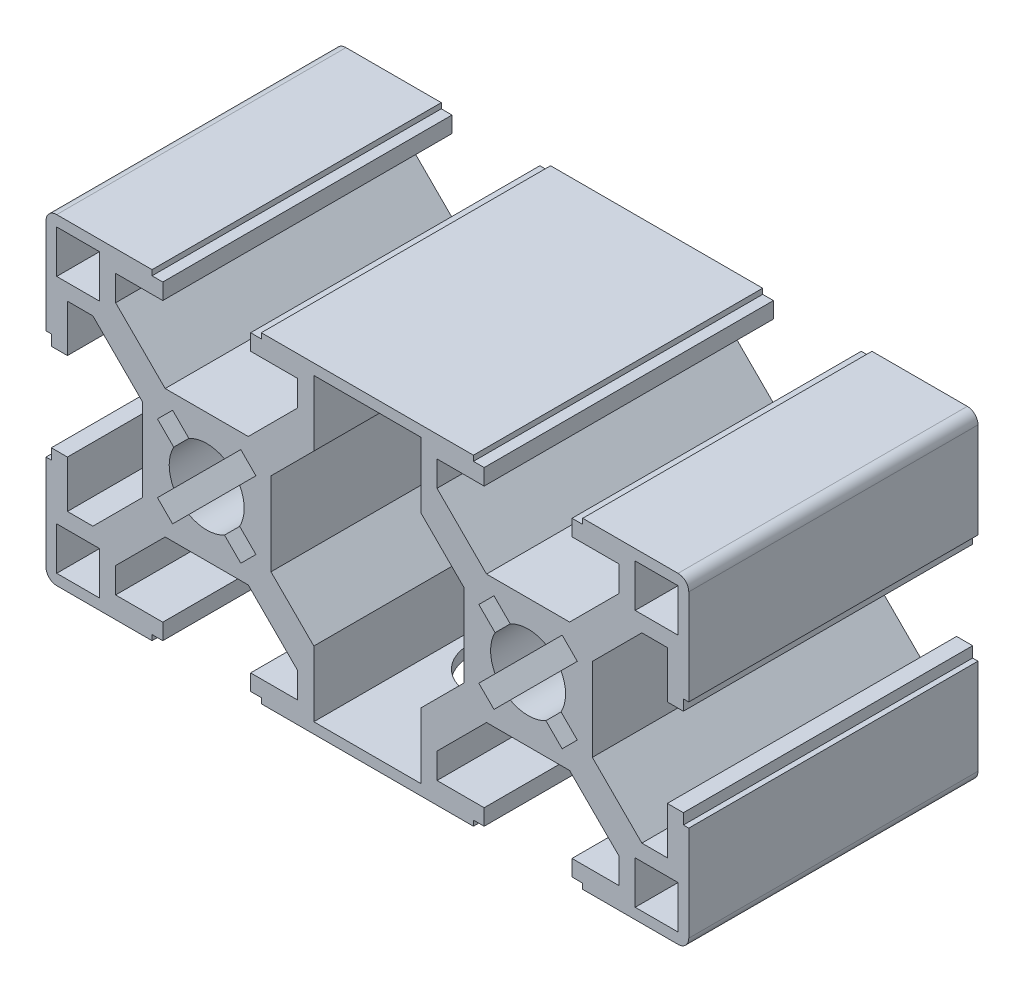
SolidWorks part; units mm, degrees
material "6063-O"
ref_plane "Plano frontal" through (0, 0, 0) normal (0, 0, 1) x (1, 0, 0)
ref_plane "Plano superior" through (0, 0, 0) normal (0, 1, 0) x (1, 0, 0)
ref_plane "Plano direito" through (0, 0, 0) normal (1, 0, 0) x (0, 0, -1)
sketch "Esboço1" plane through (0, 0, 0) normal (0, 0, 1) x (1, 0, 0)
  line L5 (0, 0) -> (-17.7944, 17.7944) construction
  line L6 (0, 3.5) -> (0, 6)
  line L8 (0, 6) -> (-3.8787, 6)
  line L9 (-3.5, 0) -> (-6, 0)
  line L48 (-6, 0) -> (-6, 3.8787)
  line L49 (-3.8787, 6) -> (-8.5, 10.6213)
  line L50 (-6, 3.8787) -> (-10.6213, 8.5)
  line L51 (0, 0) -> (-12.921, 0) construction
  line L52 (-8.5, 13) -> (-4.1, 13)
  line L53 (-4.1, 13) -> (-4.1, 14.5)
  line L54 (-4.1, 14.5) -> (-5.1, 14.5)
  line L55 (-5.1, 14.5) -> (-5.1, 15)
  line L56 (-5.1, 15) -> (-15, 15)
  line L57 (-15, 5.1) -> (-15, 15)
  line L58 (-14.5, 5.1) -> (-15, 5.1)
  line L59 (-14.5, 4.1) -> (-14.5, 5.1)
  line L60 (-13, 4.1) -> (-14.5, 4.1)
  line L61 (-13, 8.5) -> (-13, 4.1)
  line L62 (-1.6646, 3.0788) -> (-3.182, 4.5962)
  line L63 (-3.0788, 1.6646) -> (-4.5962, 3.182)
  line L64 (-4.5962, 3.182) -> (-3.182, 4.5962)
  line L65 (-8.5, 13) -> (-8.5, 10.6213)
  line L66 (-10, 14) -> (-14, 14)
  line L67 (-10, 14) -> (-10, 10)
  line L68 (-10, 10) -> (-14, 10)
  line L69 (-14, 14) -> (-14, 10)
  line L70 (-10, 14) -> (-14, 10) construction
  line L71 (-10, 10) -> (-14, 14) construction
  line L72 (-13, 8.5) -> (-10.6213, 8.5)
  circle A1 centre (0, 0) radius 3.5
  point P25 (-12, 12)
  dimension "D5" = 10.9
  dimension "D9" = 5.5
  dimension "D10" = 2
  dimension "D11" = 4
  dimension "D12" = 4
  dimension "D13" = 1
  dimension "D1" = 7
  dimension "D2" = 6
  dimension "D3" = 3
  dimension "D4" = 9.9
  dimension "D6" = 0.5
  dimension "D7" = 1.5
  dimension "D8" = 15
  dimension "D14" = 6.5
extrude "Ressalto-extrusão1" add sketch "Esboço1" along normal blind 27 contours A1 L6 L8 L49 L65 L52 L53 L54 L55 L56 L57 L58 L59 L60 L61 L72 L50 L48 L9 L63 L64 L62 L69 L66 L67 L68
sketch "Esboço3" plane through (0, 0, 0) normal (1, 0, 0) x (0, 0, -1)
  line L0 (0, 0) -> (-1000, 0) construction
  dimension "D1" = 1000
pattern_circular "PadrãoCircular1" count 4 over 360 about axis through (0, 0, 0) along (0, 0, 1) of "Ressalto-extrusão1"
pattern_linear "Padrão linear1" count 2 spacing 30 along (1, 0, 0) of "Ressalto-extrusão1", "PadrãoCircular1"
sketch "Esboço4" plane through (0, 0, 0) normal (0, 0, -1) x (-1, 0, 0)
  line L0 (-20, 14) -> (-20, -14)
  line L1 (-20, -14) -> (-10, -14)
  line L2 (-10, -14) -> (-10, 14)
  line L3 (-10, 14) -> (-20, 14)
extrude "Corte-extrusão1" cut sketch "Esboço4" against normal through all
fillet "Filete1" radius 1 4 edges at (45, -15, 13.5) (45, 15, 13.5) (-15, 15, 13.5) (-15, -15, 13.5)
sketch "Sketch1" plane through (0, -15, 0) normal (0, -1, 0) x (1, 0, 0)
  line L0 (44, 13.5) -> (-14, 13.5) construction
  line L1 (44, 0) -> (44, 27) construction
  line L2 (-14, 27) -> (-14, 0) construction
  line L3 (15, 27) -> (15, 0) construction
  line L4 (5.1, 27) -> (24.9, 27) construction
  line L5 (5.1, 0) -> (24.9, 0) construction
  circle A0 centre (33.25, 13.5) radius 2.5
  circle A1 centre (-3.25, 13.5) radius 2.5
  circle A2 centre (15, 13.5) radius 4
  dimension "D1" = 5
  dimension "D2" = 36.5
  dimension "D3" = 8
extrude "Cut-Extrude1" cut sketch "Sketch1" against normal blind 6
